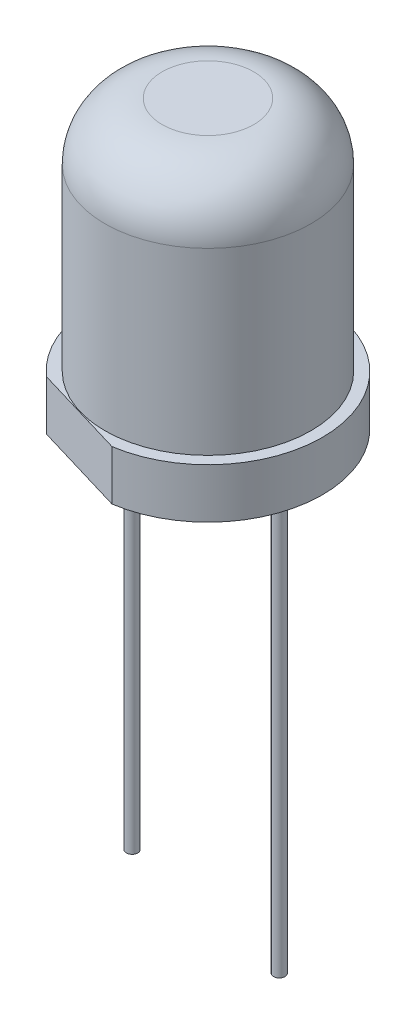
SolidWorks part; units mm, degrees
ref_plane "Ön Düzlem" through (0, 0, 0) normal (0, 0, 1) x (1, 0, 0)
ref_plane "Üst Düzlem" through (0, 0, 0) normal (0, 1, 0) x (1, 0, 0)
ref_plane "Sağ Düzlem" through (0, 0, 0) normal (1, 0, 0) x (0, 0, -1)
sketch "Çizim1" plane through (0, 0, 0) normal (0, 0, 1) x (1, 0, 0)
  line L0 (0, 0) -> (10, 0)
  line L1 (10, 0) -> (10, 4.3466)
  line L2 (10, 4.3466) -> (9, 4.3466)
  line L3 (9, 4.3466) -> (9, 20)
  line L4 (4, 25) -> (0, 25)
  line L5 (0, 25) -> (0, 0)
  arc A0 (4, 25) -> (9, 20) centre (4, 20) cw
  dimension "D2" = 10
  dimension "D1" = 5
  dimension "D3" = 1
  dimension "D4" = 25
revolve "Döndür2" add sketch "Çizim1" angle 360 about L5
sketch "Çizim2" plane through (0, 0, 0) normal (0, -1, 0) x (1, 0, 0)
  line L0 (-6.6677, 7.4527) -> (1.504, 9.8862)
  line L1 (-6.6677, 7.4527) -> (-7.5069, 10)
  line L2 (-7.5069, 10) -> (0.6161, 11.5927)
  line L3 (0.6161, 11.5927) -> (1.504, 9.8862)
  circle A0 centre (0, 0) radius 10 construction
extrude "Kes-Ekstrüzyon2" cut sketch "Çizim2" against normal blind 10
sketch3d "3B Çizim1"
  line L0 (-1.4439, 1.8533, 5.1825) -> (-1.4439, -29.9675, 5.1825)
  line L1 (0.6331, 0, -5.7812) -> (0.6331, -50.2381, -5.7812)
  point P3 (-1.4439, -14.0571, 5.1825)
ref_plane "Düzlem1" through (-1.4439, -29.9675, 5.1825) normal (0, -1, 0) x (-1, 0, 0)
sketch "Çizim4" plane through (-1.4439, -29.9675, 5.1825) normal (0, -1, 0) x (-1, 0, 0)
  circle A0 centre (0, 0) radius 0.5
  dimension "D1" = 1
sweep "Süpür1" add profiles "Çizim4" path "3B Çizim1"
sketch3d "3B Çizim2"
  line L0 (1.7938, 0, -4.4358) -> (1.7938, -42.508, -4.4358)
ref_plane "Düzlem2" through (1.7938, -42.508, -4.4358) normal (0, -1, 0) x (-1, 0, 0)
sketch "Çizim6" plane through (1.7938, -42.508, -4.4358) normal (0, -1, 0) x (-1, 0, 0)
  circle A0 centre (0, 0) radius 0.5
  dimension "D1" = 1
sweep "Süpür2" add profiles "Çizim6" path "3B Çizim2"
